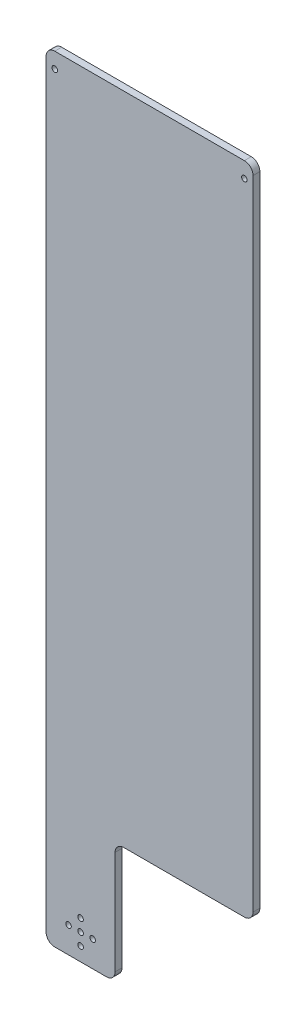
SolidWorks part; units mm, degrees
ref_plane "前视基准面" through (0, 0, 0) normal (0, 0, 1) x (1, 0, 0)
ref_plane "上视基准面" through (0, 0, 0) normal (0, 1, 0) x (1, 0, 0)
ref_plane "右视基准面" through (0, 0, 0) normal (1, 0, 0) x (0, 0, -1)
other "Configuration Table"
sketch "草图2" plane through (0, 0, 0) normal (0, 0, 1) x (1, 0, 0)
  line L0 (20, 23.7722) -> (20, 2.2737) construction
  line L1 (0, 0) -> (40, 0)
  line L2 (0, 0) -> (0, 450)
  line L3 (0, 450) -> (40, 450)
  line L4 (40, 0) -> (40, 70)
  line L5 (13, 15) -> (30.8808, 15) construction
  line L6 (40, 450) -> (120, 450)
  line L7 (120, 450) -> (120, 70)
  line L8 (120, 70) -> (40, 70)
  circle A0 centre (20, 8) radius 1.6
  circle A1 centre (20, 22) radius 1.6
  circle A2 centre (27, 15) radius 1.6
  circle A3 centre (13, 15) radius 1.6
  circle A10 centre (20, 15) radius 1.6
  circle A15 centre (115, 441) radius 1.6
  circle A16 centre (5, 441) radius 1.6
  point P17 (20, 0)
  dimension "D3" = 3.2
  dimension "D13" = 3.2
  dimension "D8" = 3.2
  dimension "D14" = 9
  dimension "D1" = 40
  dimension "D2" = 450
  dimension "D4" = 14
  dimension "D5" = 14
  dimension "D6" = 15
  dimension "D9" = 5
  dimension "D10" = 100
  dimension "D11" = 380
  dimension "D12" = 9
  dimension "D19" = 5
extrude "凸台-拉伸1" add sketch "草图2" along normal blind 4
fillet "圆角1" radius 5 6 edges at (0, 0, 2) (40, 0, 2) (40, 70, 2) (120, 70, 2) (120, 450, 2) (0, 450, 2)
